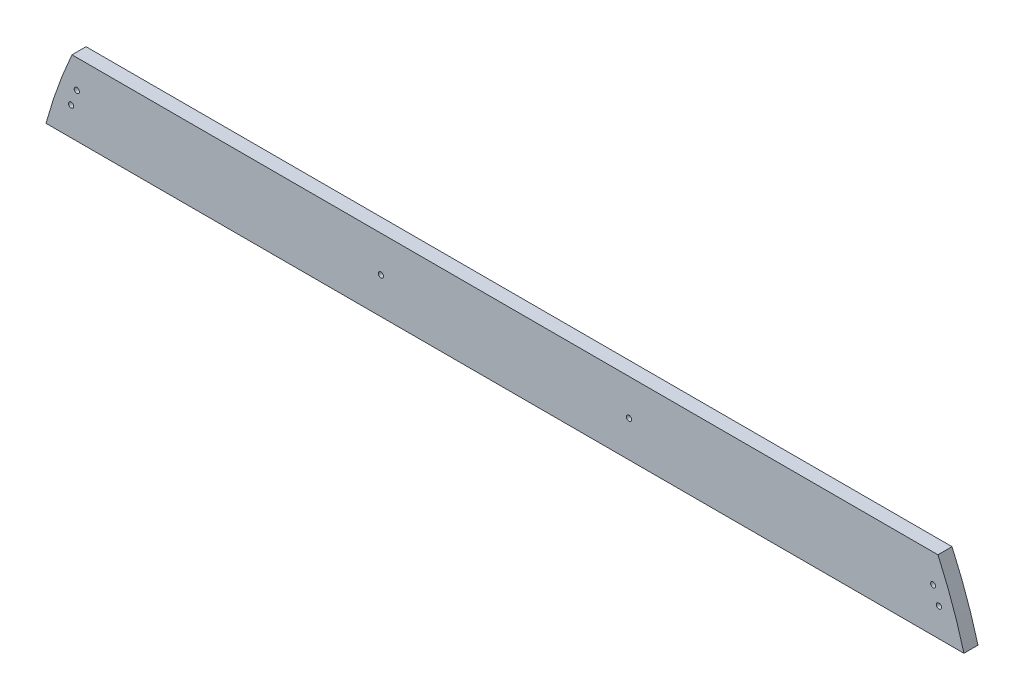
SolidWorks part; units mm, degrees
ref_plane "Front Plane" through (0, 0, 0) normal (0, 0, 1) x (1, 0, 0)
ref_plane "Top Plane" through (0, 0, 0) normal (0, 1, 0) x (1, 0, 0)
ref_plane "Right Plane" through (0, 0, 0) normal (1, 0, 0) x (0, 0, -1)
sketch "Sketch1" plane through (0, 0, 0) normal (0, 0, 1) x (1, 0, 0)
  line L0 (-550.0361, 196.85) -> (550.0361, 196.85) construction
  line L1 (-532.0375, 241.3) -> (532.0375, 241.3)
  line L3 (-563.9715, 152.4) -> (563.9715, 152.4)
  arc A0 (-532.0375, 241.3) -> (-563.9715, 152.4) centre (0, 0) ccw
  arc A1 (563.9715, 152.4) -> (532.0375, 241.3) centre (0, 0) ccw
  circle A2 centre (0, 0) radius 565.15 construction
  circle A3 centre (-526.1215, 206.375) radius 3.175
  circle A4 centre (-533.2015, 187.325) radius 3.175
  circle A5 centre (526.1215, 206.375) radius 3.175
  circle A6 centre (533.2015, 187.325) radius 3.175
  dimension "D1" = 1168.4
  dimension "D4" = 1130.3
  dimension "D6" = 6.35
  dimension "D9" = 6.35
  dimension "D2" = 152.4
  dimension "D3" = 88.9
  dimension "D5" = 19.05
  dimension "D7" = 9.525
  dimension "D8" = 196.85
  dimension "D10" = 19.05
  dimension "D11" = 9.525
extrude "Boss-Extrude1" add sketch "Sketch1" along normal blind 17.272 contours L3 A1 L1 A0 A6 A5 A4 A3
sketch "Sketch2" [suppressed] plane through (0, 0, 0) normal (0, 0, -1) x (-1, 0, 0)
  line L0 (549.8043, 196.85) -> (-549.8043, 196.85) construction
  line L1 (0, 152.4) -> (0, 241.3) construction
  line L2 (557.3911, 152.4) -> (-557.3911, 152.4) construction
  line L3 (525.0571, 241.3) -> (-525.0571, 241.3) construction
  circle A2 centre (0, 196.85) radius 3.175
  circle A3 centre (203.2, 196.85) radius 3.175
  circle A4 centre (-203.2, 196.85) radius 3.175
  point P15 (0, 196.85)
  dimension "D2" = 203.2
  dimension "D3" = 6.35
  dimension "D1" = 203.2
extrude "Cut-Extrude1" [suppressed] cut sketch "Sketch2" against normal up to next
sketch "Sketch3" plane through (0, 0, 17.272) normal (0, 0, 1) x (1, 0, 0)
  line L0 (0, 241.3) -> (0, 152.4) construction
  line L1 (-532.0375, 241.3) -> (532.0375, 241.3) construction
  line L2 (-563.9715, 152.4) -> (563.9715, 152.4) construction
  line L3 (0, 196.85) -> (-549.8047, 196.85) construction
  line L4 (0, 196.85) -> (549.8047, 196.85) construction
  circle A3 centre (152.4, 196.85) radius 3.175
  circle A4 centre (-152.4, 196.85) radius 3.175
  dimension "D1" = 152.4
  dimension "D3" = 6.35
  dimension "D2" = 152.4
  dimension "D4" = 6.35
extrude "Cut-Extrude2" cut sketch "Sketch3" against normal up to next
